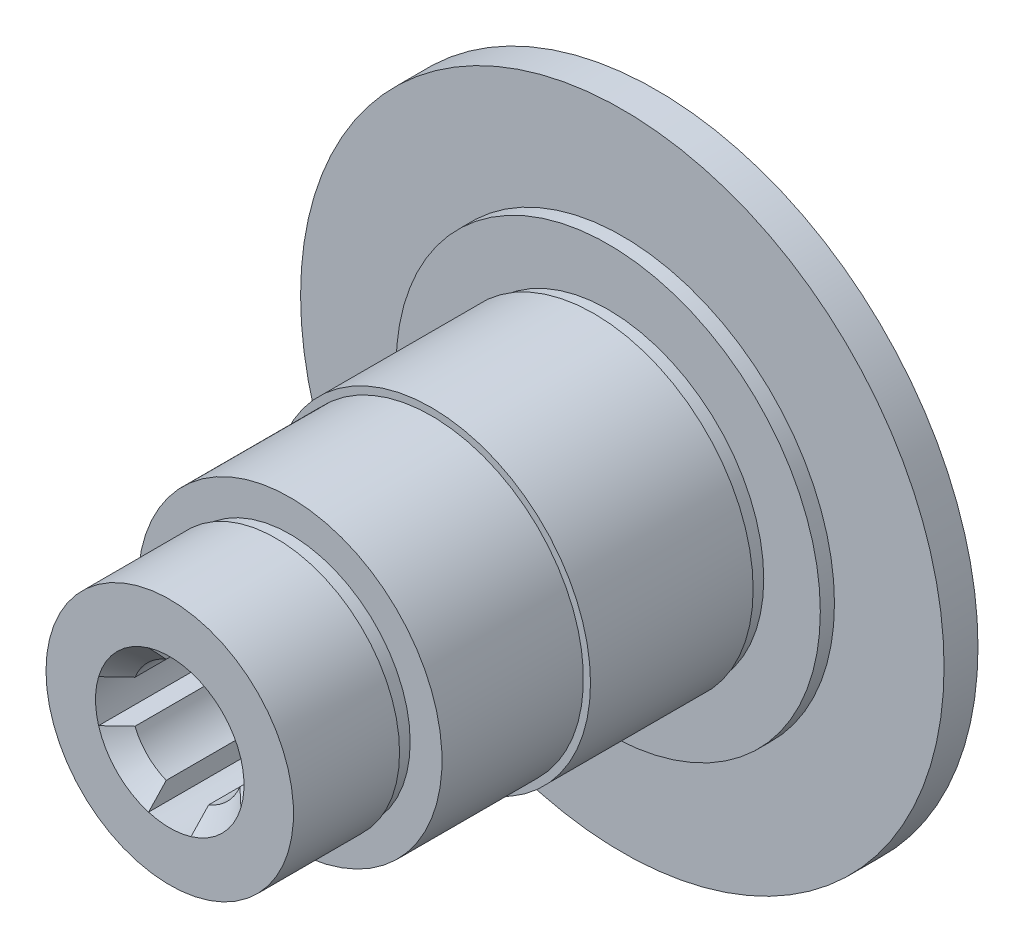
SolidWorks part; units mm, degrees
ref_plane "前视基准面" through (0, 0, 0) normal (0, 0, 1) x (1, 0, 0)
ref_plane "上视基准面" through (0, 0, 0) normal (0, 1, 0) x (1, 0, 0)
ref_plane "右视基准面" through (0, 0, 0) normal (1, 0, 0) x (0, 0, -1)
sketch "草图1" plane through (0, 0, 0) normal (1, 0, 0) x (0, 0, -1)
  line L0 (0, 0) -> (0, 17.5)
  line L1 (0, 55) -> (0, -55) construction
  line L2 (0, 17.5) -> (17, 17.5)
  line L3 (17, 17.5) -> (17, 21.5)
  line L4 (17, 21.5) -> (37, 21.5)
  line L5 (37, 21.5) -> (37, 22.5)
  line L6 (37, 22.5) -> (62, 22.5)
  line L7 (62, 22.5) -> (62, 30)
  line L8 (62, 30) -> (64, 30)
  line L9 (64, 30) -> (64, 45.5)
  line L10 (64, 45.5) -> (68.7961, 45.5)
  line L11 (68.7961, 45.5) -> (85, 13)
  line L12 (85, 13) -> (85, 0)
  line L13 (55, 0) -> (-55, 0) construction
  line L14 (85, 0) -> (0, 0) construction
  line L15 (0, 0) -> (85, 0)
  point P15 (71.0277, 45.5)
  dimension "D1" = 91
  dimension "D2" = 26
  dimension "D3" = 60
  dimension "D4" = 45
  dimension "D5" = 43
  dimension "D6" = 35
  dimension "D7" = 17
  dimension "D8" = 25
  dimension "D9" = 62
  dimension "D10" = 2
  dimension "D11" = 85
  dimension "D12" = 26.5
revolve "旋转1" add sketch "草图1" angle 360 about L14
sketch "草图2" plane through (0, 0, -17) normal (0, 0, 1) x (1, 0, 0)
  circle A2 centre (0, 0) radius 17
  circle A3 centre (0, 0) radius 17
  dimension "D1" = 0.5
extrude "切除-拉伸1" cut sketch "草图2" along normal blind 2 flip side to cut
sketch "草图3" plane through (0, 0, -62) normal (0, 0, 1) x (1, 0, 0)
  circle A2 centre (0, 0) radius 22
  circle A3 centre (0, 0) radius 22
  dimension "D1" = 0.5
extrude "切除-拉伸2" cut sketch "草图3" along normal blind 2 flip side to cut
sketch "草图4" plane through (0, 0, 0) normal (0, 0, 1) x (1, 0, 0)
  line L0 (0, 0) -> (0, 13.0893) construction
  line L1 (0, -46.75) -> (0, 46.75) construction
  line L2 (-3, 10.0623) -> (-3, 7.4162)
  line L3 (3, 10.0623) -> (3, 7.4162)
  line L4 (10.0623, 3) -> (7.4162, 3)
  line L5 (10.0623, -3) -> (7.4162, -3)
  line L6 (3, -10.0623) -> (3, -7.4162)
  line L7 (-3, -10.0623) -> (-3, -7.4162)
  line L8 (-10.0623, -3) -> (-7.4162, -3)
  line L9 (-10.0623, 3) -> (-7.4162, 3)
  arc A0 (-3, 7.4162) -> (-7.4162, 3) centre (0, 0) ccw
  arc A1 (3, 10.0623) -> (-3, 10.0623) centre (0, 0) ccw
  arc A2 (3, 7.4162) -> (0, 8) centre (0, 0) ccw construction
  arc A3 (0, 8) -> (-3, 7.4162) centre (0, 0) ccw construction
  arc A4 (-3, 10.0623) -> (3, 10.0623) centre (0, 0) ccw construction
  arc A5 (10.0623, -3) -> (10.0623, 3) centre (0, 0) ccw
  arc A6 (-3, -10.0623) -> (3, -10.0623) centre (0, 0) ccw
  arc A7 (-10.0623, 3) -> (-10.0623, -3) centre (0, 0) ccw
  arc A8 (-7.4162, 3) -> (-7.4162, -3) centre (0, 0) ccw construction
  arc A9 (-7.4162, -3) -> (-3, -7.4162) centre (0, 0) ccw
  arc A10 (7.4162, -3) -> (7.4162, 3) centre (0, 0) ccw construction
  arc A11 (7.4162, 3) -> (3, 7.4162) centre (0, 0) ccw
  arc A12 (-3, -7.4162) -> (3, -7.4162) centre (0, 0) ccw construction
  arc A13 (3, -7.4162) -> (7.4162, -3) centre (0, 0) ccw
  dimension "D1" = 16
  dimension "D2" = 21
  dimension "D3" = 6
  dimension "D4" = 4
extrude "切除-拉伸3" cut sketch "草图4" against normal through all
chamfer "倒角1" distance 2.5 angle 45 8 edges at (5.6569, -5.6569, -85) (5.6569, 5.6569, -85) (-5.6569, 5.6569, -85) (-5.6569, -5.6569, -85) (-5.6569, -5.6569, 0) (5.6569, -5.6569, 0) (5.6569, 5.6569, 0) (-5.6569, 5.6569, 0)
